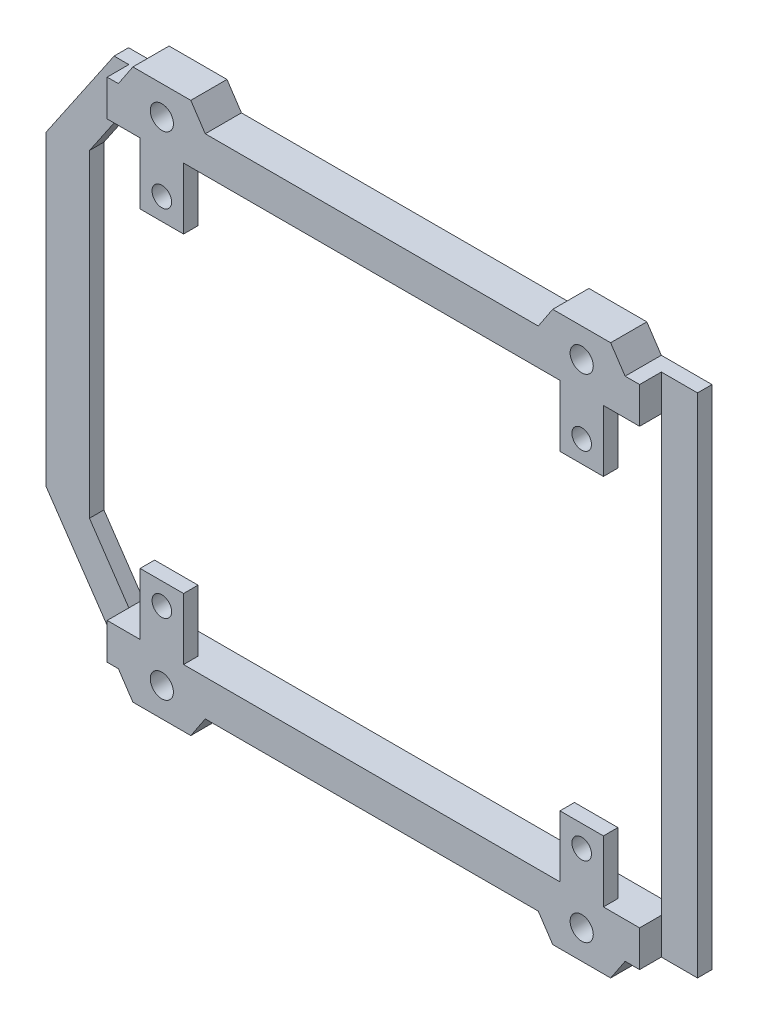
SolidWorks part; units mm, degrees
material "PET"
ref_plane "Front Plane" through (0, 0, 0) normal (0, 0, 1) x (1, 0, 0)
ref_plane "Top Plane" through (0, 0, 0) normal (0, 1, 0) x (1, 0, 0)
ref_plane "Right Plane" through (0, 0, 0) normal (1, 0, 0) x (0, 0, -1)
sketch "rpi_sketch" plane through (0, 0, 0) normal (0, 0, 1) x (1, 0, 0)
  line L1 (-29, -24.5) -> (29, -24.5)
  line L2 (-29, -24.5) -> (-29, 24.5)
  line L3 (-29, 24.5) -> (29, 24.5)
  line L4 (29, -24.5) -> (29, 24.5)
  line L5 (-29, -24.5) -> (29, 24.5) construction
  line L6 (-29, 24.5) -> (29, -24.5) construction
  line L7 (-32.5, -28) -> (52.5, -28)
  line L8 (-32.5, -28) -> (-32.5, 28)
  line L9 (-32.5, 28) -> (52.5, 28)
  line L10 (52.5, -28) -> (52.5, 28)
  circle A0 centre (-29, 24.5) radius 1.35
  circle A1 centre (29, 24.5) radius 1.35
  circle A2 centre (29, -24.5) radius 1.35
  circle A3 centre (-29, -24.5) radius 1.35
  point P0 (0, 0)
  dimension "D4" = 2.7
  dimension "D1" = 58
  dimension "D2" = 49
  dimension "D3" = 3.5
  dimension "D5" = 3.5
  dimension "D6" = 56
  dimension "D7" = 85
sketch "Sketch3" plane through (0, 0, 0) normal (0, 0, 1) x (1, 0, 0)
  line L0 (-26, 21.5) -> (-26, 30)
  line L1 (-26, 30) -> (26, 30)
  line L2 (26, 30) -> (26, 21.5)
  line L3 (26, 21.5) -> (32, 21.5)
  line L4 (32, 21.5) -> (32, 30)
  line L5 (32, 30) -> (37, 30)
  line L6 (37, 30) -> (37, -30)
  line L7 (37, -30) -> (32, -30)
  line L8 (32, -30) -> (32, -21.5)
  line L9 (32, -21.5) -> (26, -21.5)
  line L10 (26, -21.5) -> (26, -30)
  line L11 (26, -30) -> (-26, -30)
  line L12 (-26, -30) -> (-26, -21.5)
  line L13 (-26, -21.5) -> (-32, -21.5)
  line L14 (-32, -21.5) -> (-32, -30)
  line L15 (-32, -30) -> (-36.5543, -30)
  line L16 (-36.5543, -30) -> (-42, -22)
  line L17 (-42, -22) -> (-42, 22)
  line L18 (-42, 22) -> (-36.5543, 30)
  line L19 (-36.5543, 30) -> (-32, 30)
  line L20 (-32, 30) -> (-32, 21.5)
  line L21 (-32, 21.5) -> (-26, 21.5)
  line L22 (-48, 21.1827) -> (-48, -21.1827)
  line L23 (-48, -21.1827) -> (-38.5944, -35)
  line L24 (-38.5944, -35) -> (42, -35)
  line L25 (42, -35) -> (42, 35)
  line L26 (42, 35) -> (-38.5944, 35)
  line L27 (-38.5944, 35) -> (-48, 21.1827)
  line L28 (-29, -24.5) -> (-29, 24.5) construction
  line L29 (29, -24.5) -> (29, 24.5) construction
  line L30 (-32.5, 28) -> (52.5, 28) construction
  line L31 (-32.5, -28) -> (52.5, -28) construction
  line L32 (-29, -24.5) -> (29, -24.5) construction
  point P27 (-29, 21.5)
  point P31 (-29, -21.5)
  point P32 (29, -21.5)
  dimension "D12" = 3
  dimension "D1" = 2
  dimension "D2" = 2
  dimension "D3" = 5
  dimension "D4" = 5
  dimension "D5" = 6
  dimension "D6" = 5
  dimension "D7" = 10
  dimension "D8" = 8
  dimension "D9" = 16
  dimension "D10" = 5
  dimension "D11" = 4.5
extrude "body" add sketch "Sketch3" along normal blind 5
sketch "Sketch4" plane through (0, 0, 0) normal (0, 0, 1) x (1, 0, 0)
  line L0 (-35, 35) -> (-33, 38)
  line L1 (42, 35) -> (-38.5944, 35) construction
  line L2 (-33, 38) -> (-25, 38)
  line L3 (-25, 38) -> (-23, 35)
  line L4 (-23, 35) -> (-35, 35)
  line L9 (-29, -24.5) -> (-29, 24.5) construction
  point P6 (-29, 38)
  point P10 (-29, 35)
  dimension "D1" = 12
  dimension "D2" = 3
  dimension "D3" = 8
extrude "side_extrusion" add sketch "Sketch4" along normal up to vertex (5 mm away)
sketch "Sketch5" plane through (0, 0, 5) normal (0, 0, 1) x (1, 0, 0)
  line L0 (-25, 38) -> (-33, 38) construction
  line L1 (-29, -24.5) -> (-29, 24.5) construction
  point P0 (-29, 34)
  dimension "D1" = 4
hole_wizard "mounting_hole" positions "Sketch5" profile "Sketch6" hole size "M3" standard "DIN" end condition through all
sketch "Sketch6" plane through (-29, 34, 5) normal (1, 0, 0) x (0, -1, 0)
  line L0 (0, 0) -> (0, 5)
  line L1 (0, 5) -> (1.6, 5)
  line L2 (1.6, 5) -> (1.6, 0)
  line L5 (1.6, 0) -> (0, 0)
  line L11 (0, -6.35) -> (0, 107.95) construction
  dimension "Thru Hole Dia." = 3.2
  dimension "Thru Hole Depth" = 5
sketch "Sketch7" plane through (-26, 0, 0) normal (1, 0, 0) x (0, 0, -1)
  line L0 (-5, 30) -> (0, 30) construction
  line L1 (0, 21.5) -> (-3, 21.5)
  line L2 (0, 21.5) -> (0, 30)
  line L3 (0, 30) -> (-3, 30)
  line L4 (-3, 21.5) -> (-3, 30)
  dimension "D1" = 3
extrude "mounting_cutout" cut sketch "Sketch7" against normal up to next
sketch "Sketch8" plane through (0, 0, 5) normal (0, 0, 1) x (1, 0, 0)
  circle A0 centre (-29, 24.5) radius 1.35
extrude "mounting_hole_cutout" cut sketch "Sketch8" against normal through all
mirror "mounting_mirror1" about plane through (0, 0, 0) normal (1, 0, 0) of "mounting_hole_cutout", "mounting_cutout", "mounting_hole", "side_extrusion"
mirror "mounting_mirror2" about plane through (0, 0, 0) normal (0, 1, 0) of "mounting_mirror1", "side_extrusion", "mounting_hole", "mounting_cutout", "mounting_hole_cutout"
sketch "Sketch9" plane through (0, 0, 5) normal (0, 0, 1) x (1, 0, 0)
  line L0 (42, 35) -> (35, 35) construction
  line L1 (42, -35) -> (37, -35)
  line L2 (42, -35) -> (42, 35)
  line L3 (42, 35) -> (37, 35)
  line L4 (37, -35) -> (37, 35)
  line L5 (37, -30) -> (37, 30) construction
  line L6 (-38.5944, -35) -> (-35, -35) construction
  line L7 (-36.5543, -35) -> (-48, -35)
  line L8 (-36.5543, -35) -> (-36.5543, 35)
  line L9 (-36.5543, 35) -> (-48, 35)
  line L10 (-48, -35) -> (-48, 35)
  line L11 (-35, 35) -> (-38.5944, 35) construction
  line L12 (-48, 21.1827) -> (-48, -21.1827) construction
extrude "rpi_spacing_cutout" cut sketch "Sketch9" against normal blind 3
